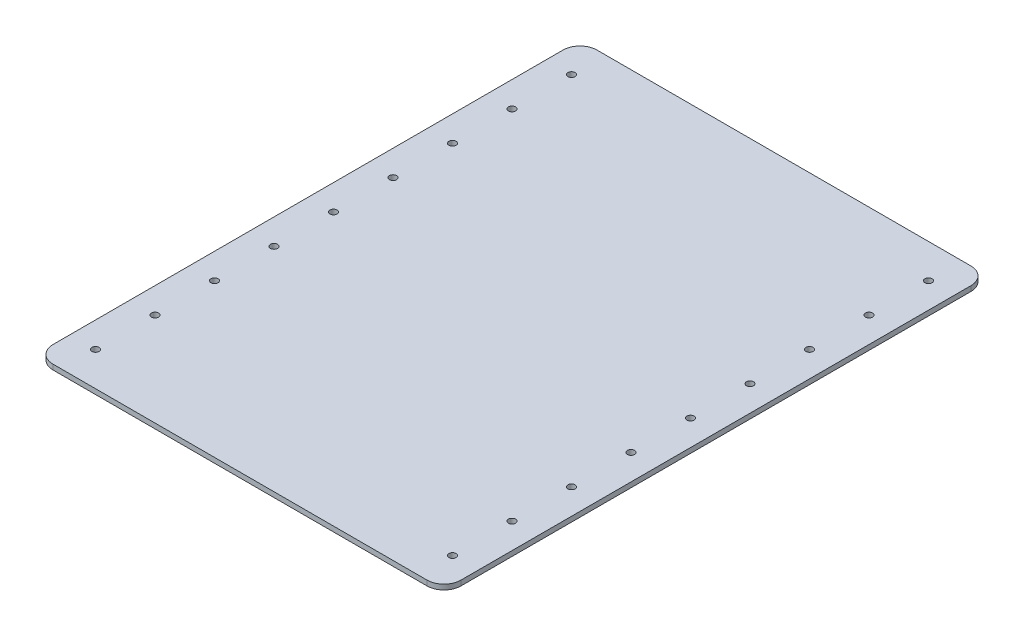
SolidWorks part; units mm, degrees
material "Thornel Mat VMA"
ref_plane "前视基准面" through (0, 0, 0) normal (0, 0, 1) x (1, 0, 0)
ref_plane "上视基准面" through (0, 0, 0) normal (0, 1, 0) x (1, 0, 0)
ref_plane "右视基准面" through (0, 0, 0) normal (1, 0, 0) x (0, 0, -1)
sketch "草图1" plane through (0, 0, 0) normal (0, 1, 0) x (1, 0, 0)
  line L1 (-120, 160) -> (120, 160)
  line L2 (-120, 160) -> (-120, -160)
  line L3 (-120, -160) -> (120, -160)
  line L4 (120, 160) -> (120, -160)
  line L5 (-120, 160) -> (120, -160) construction
  line L6 (-120, -160) -> (120, 160) construction
  point P0 (0, 0)
  dimension "D1" = 320
  dimension "D2" = 240
extrude "凸台-拉伸1" add sketch "草图1" along normal blind 3
fillet "圆角1" radius 10 4 edges at (-120, 1.5, -160) (120, 1.5, -160) (120, 1.5, 160) (-120, 1.5, 160)
sketch "草图2" plane through (0, 3, 0) normal (0, 1, 0) x (1, 0, 0)
  line L0 (-105, -833.0003) -> (-105, 49166.9997) construction
  line L1 (-105, 140) -> (-105, 105) construction
  line L2 (110, 160) -> (-110, 160) construction
  line L3 (0, 0) -> (0, -103.271) construction
  line L4 (105, 140) -> (105, 105) construction
  circle A0 centre (-105, 140) radius 2.1
  circle A1 centre (-105, 105) radius 2.1
  circle A2 centre (-105, 70) radius 2.1
  circle A3 centre (-105, 35) radius 2.1
  circle A4 centre (-105, 0) radius 2.1
  circle A5 centre (-105, -35) radius 2.1
  circle A6 centre (-105, -70) radius 2.1
  circle A7 centre (-105, -105) radius 2.1
  circle A8 centre (-105, -140) radius 2.1
  circle A9 centre (105, -140) radius 2.1
  circle A10 centre (105, -105) radius 2.1
  circle A11 centre (105, -70) radius 2.1
  circle A12 centre (105, -35) radius 2.1
  circle A13 centre (105, 0) radius 2.1
  circle A14 centre (105, 35) radius 2.1
  circle A15 centre (105, 70) radius 2.1
  circle A16 centre (105, 105) radius 2.1
  circle A17 centre (105, 140) radius 2.1
  dimension "D1" = 4.2
  dimension "D2" = 20
  dimension "D3" = 15
  dimension "D5" = 35
  dimension "D4" = 9
extrude "切除-拉伸1" cut sketch "草图2" against normal blind 3
